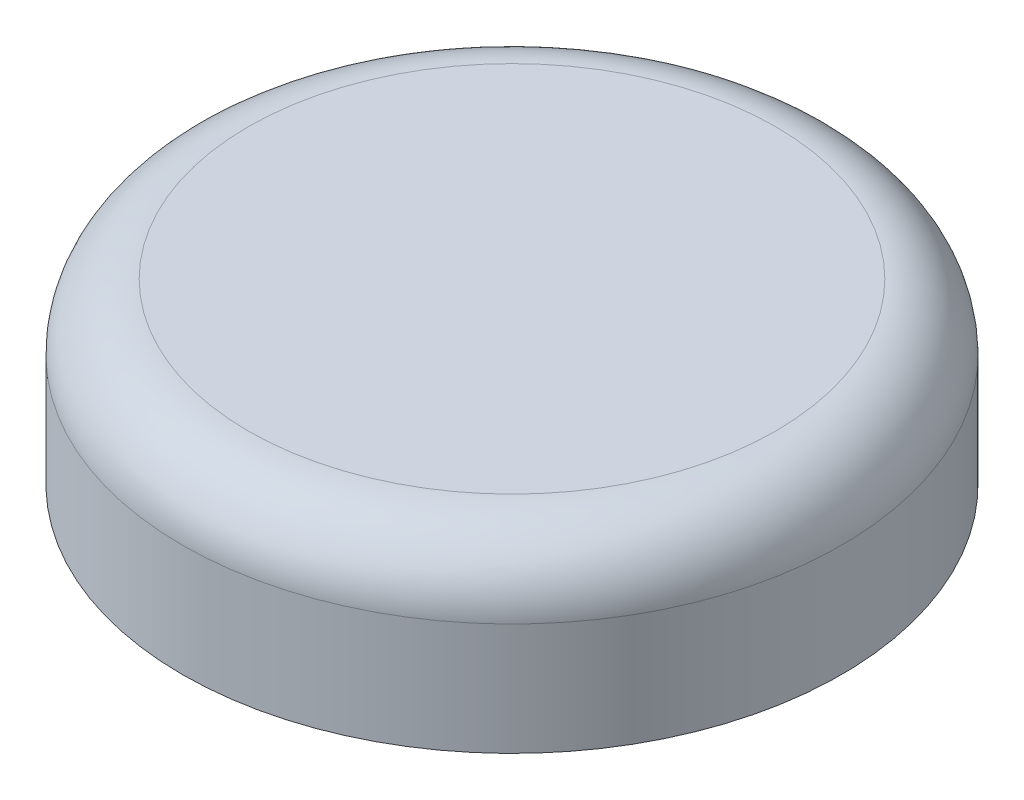
SolidWorks part; units mm, degrees
ref_plane "Plan de face" through (0, 0, 0) normal (0, 0, 1) x (1, 0, 0)
ref_plane "Plan de dessus" through (0, 0, 0) normal (0, 1, 0) x (1, 0, 0)
ref_plane "Plan de droite" through (0, 0, 0) normal (1, 0, 0) x (0, 0, -1)
sketch "Esquisse2" plane through (0, 0, 0) normal (0, 1, 0) x (1, 0, 0)
  circle A0 centre (0, 0) radius 5
  dimension "D1" = 10
extrude "Boss.-Extru.1" add sketch "Esquisse2" along normal blind 2.7
fillet "Congé1" radius 1 1 edges at (0, 2.7, 5)
